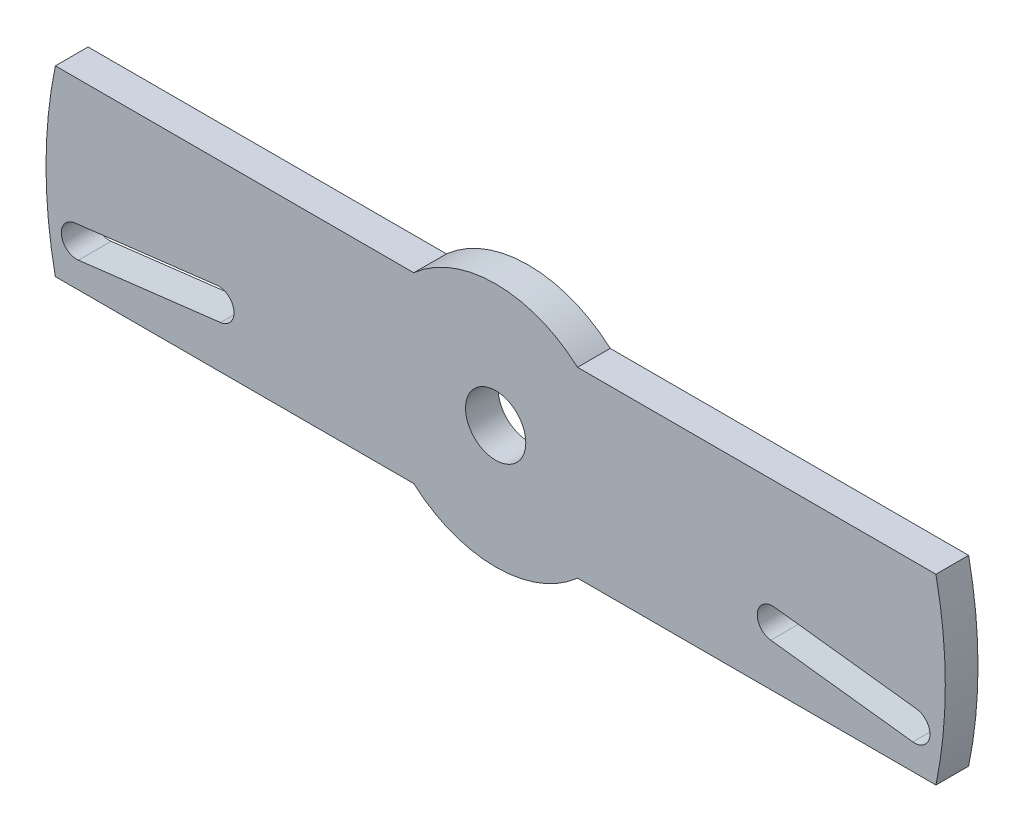
SolidWorks part; units mm, degrees
ref_plane "Спереди" through (0, 0, 0) normal (0, 0, 1) x (1, 0, 0)
ref_plane "Сверху" through (0, 0, 0) normal (0, 1, 0) x (1, 0, 0)
ref_plane "Справа" through (0, 0, 0) normal (1, 0, 0) x (0, 0, -1)
sketch "Эскиз1" plane through (0, 0, 0) normal (0, 0, 1) x (1, 0, 0)
  line L0 (0, -12) -> (0, 12) construction
  line L1 (-44, 0) -> (44, 0) construction
  line L4 (-43.0836, 8.9334) -> (0, 12) construction
  line L5 (-43.0836, -8.9334) -> (0, -12) construction
  line L6 (-41.1786, -3.4277) -> (-27.2782, -1.7607)
  line L7 (-40.8214, -6.4064) -> (-26.921, -4.7393)
  line L8 (-41, -4.917) -> (0, 0) construction
  line L9 (-41, 4.917) -> (0, 0) construction
  line L10 (-40.8214, 6.4064) -> (-26.921, 4.7393) construction
  line L11 (-41.1786, 3.4277) -> (-27.2782, 1.7607) construction
  line L12 (-43.0836, 8.9334) -> (-8.0121, 8.9334)
  line L13 (-43.0836, -8.9334) -> (-8.0121, -8.9334)
  line L14 (41.1786, 3.4277) -> (27.2782, 1.7607) construction
  line L15 (40.8214, 6.4064) -> (26.921, 4.7393) construction
  line L16 (43.0836, -8.9334) -> (8.0121, -8.9334)
  line L17 (43.0836, 8.9334) -> (8.0121, 8.9334)
  line L18 (40.8214, -6.4064) -> (26.921, -4.7393)
  line L19 (41.1786, -3.4277) -> (27.2782, -1.7607)
  arc A0 (-43.0836, 8.9334) -> (-43.0836, -8.9334) centre (0, 0) ccw
  arc A2 (-41.1786, -3.4277) -> (-40.8214, -6.4064) centre (-41, -4.917) ccw
  arc A3 (-26.921, -4.7393) -> (-27.2782, -1.7607) centre (-27.0996, -3.25) ccw
  circle A4 centre (-27.0996, 3.25) radius 1.5 construction
  circle A5 centre (-41, 4.917) radius 1.5 construction
  arc A7 (-27.0996, 3.25) -> (-27.0996, -3.25) centre (0, 0) ccw construction
  arc A8 (27.0996, 3.25) -> (27.0996, -3.25) centre (0, 0) cw construction
  arc A9 (41.1786, 3.4277) -> (40.8214, 6.4064) centre (41, 4.917) ccw construction
  arc A10 (26.921, 4.7393) -> (27.2782, 1.7607) centre (27.0996, 3.25) ccw construction
  arc A11 (26.921, -4.7393) -> (27.2782, -1.7607) centre (27.0996, -3.25) cw
  arc A12 (41.1786, -3.4277) -> (40.8214, -6.4064) centre (41, -4.917) cw
  arc A13 (43.0836, 8.9334) -> (43.0836, -8.9334) centre (0, 0) cw
  arc A14 (-8.0121, -8.9334) -> (8.0121, -8.9334) centre (0, 0) ccw
  arc A15 (8.0121, 8.9334) -> (-8.0121, 8.9334) centre (0, 0) ccw
  circle A16 centre (0, 0) radius 2.95
  point P54 (0, 12)
  dimension "D3" = 3
  dimension "D4" = 14
  dimension "D5" = 14
  dimension "D8" = 5.9
  dimension "D1" = 12
  dimension "D2" = 44
  dimension "D6" = 6.5
  dimension "D7" = 41
extrude "Бобышка-Вытянуть1" add sketch "Эскиз1" along normal blind 3.2
sketch "Эскиз2" plane through (0, 0, 3.2) normal (0, 0, 1) x (1, 0, 0)
  line L0 (-44, 0) -> (44, 0) construction
  arc A0 (-43.0836, 8.9334) -> (-43.0836, -8.9334) centre (0, 0) ccw construction
  arc A1 (43.0836, -8.9334) -> (43.0836, 8.9334) centre (0, 0) ccw construction
